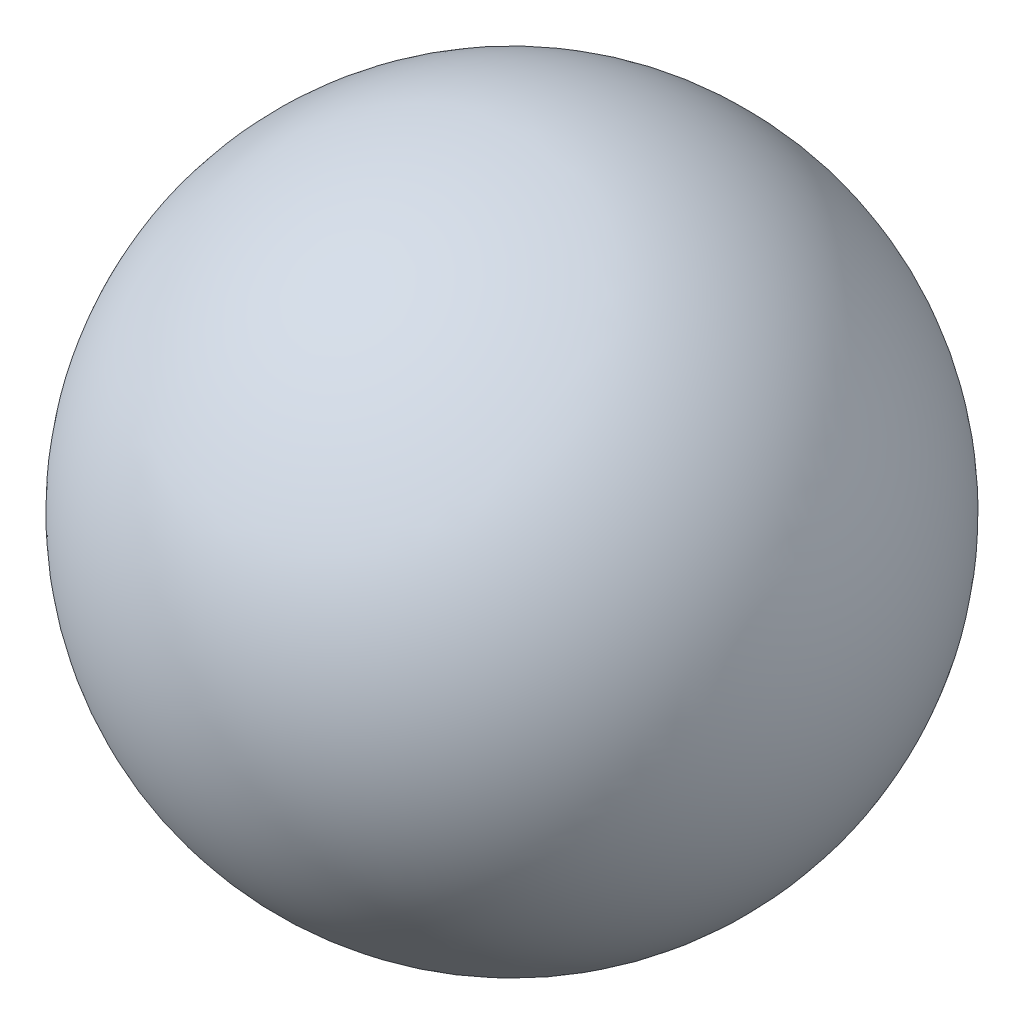
SolidWorks part; units mm, degrees
ref_plane "Front Plane" through (0, 0, 0) normal (0, 0, 1) x (1, 0, 0)
ref_plane "Top Plane" through (0, 0, 0) normal (0, 1, 0) x (1, 0, 0)
ref_plane "Right Plane" through (0, 0, 0) normal (1, 0, 0) x (0, 0, -1)
sketch "Sketch1" plane through (0, 0, 0) normal (0, 0, 1) x (1, 0, 0)
  line L0 (-6.35, 0) -> (6.35, 0)
  arc A0 (-6.35, 0) -> (6.35, 0) centre (0, 0) cw
  dimension "D1" = 6.35
  dimension "D2" = 12.7
revolve "Revolve1" add sketch "Sketch1" angle 360 about L0
